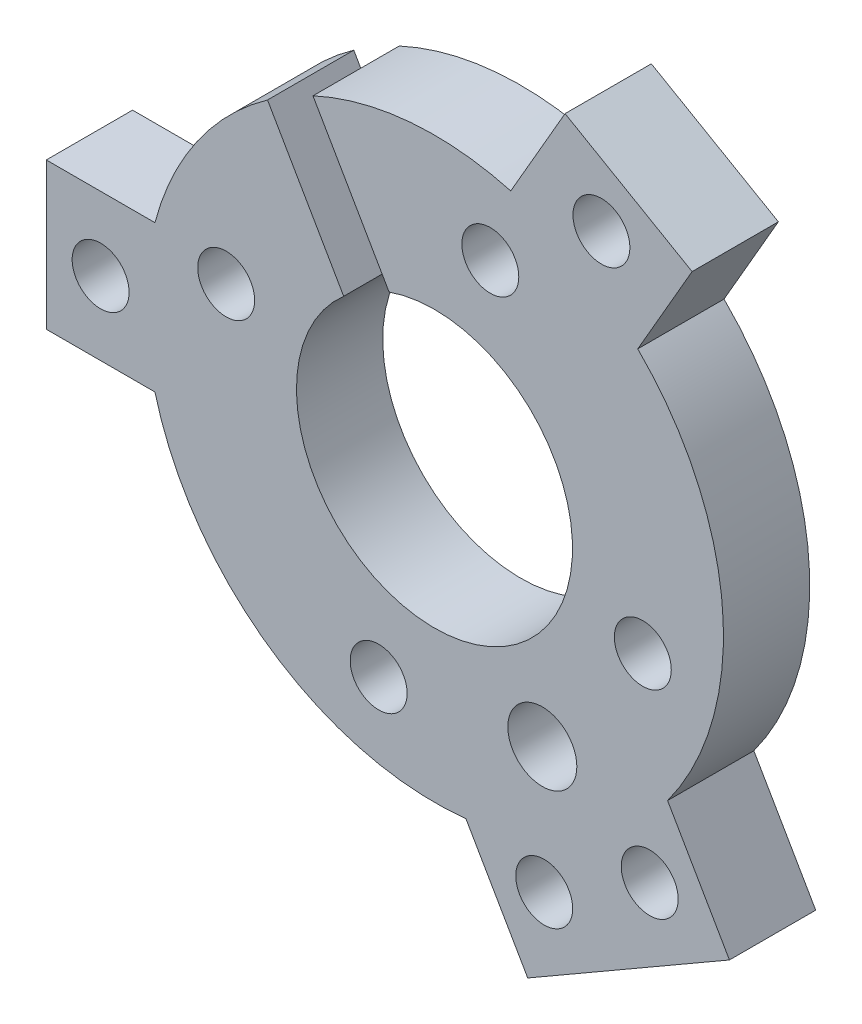
SolidWorks part; units mm, degrees
material "PET"
ref_plane "Alzado" through (0, 0, 0) normal (0, 0, 1) x (1, 0, 0)
ref_plane "Planta" through (0, 0, 0) normal (0, 1, 0) x (1, 0, 0)
ref_plane "Vista lateral" through (0, 0, 0) normal (1, 0, 0) x (0, 0, -1)
sketch "Croquis1" plane through (0, 0, 0) normal (0, 0, 1) x (1, 0, 0)
  line L0 (26.6913, -19.2308) -> (34.1913, -32.2211)
  line L1 (15.1388, 43.2211) -> (29.8612, 34.7211)
  line L2 (15.1388, 43.2211) -> (7.6388, 30.2308)
  line L3 (7.6388, 30.2308) -> (22.3612, 21.7308)
  line L4 (29.8612, 34.7211) -> (22.3612, 21.7308)
  line L5 (0, 0) -> (-34.8066, 60.2868) construction
  line L6 (0, 0) -> (-30.1609, -52.2402) construction
  line L11 (26.6913, -19.2308) -> (3.3087, -32.7308)
  line L12 (3.3087, -32.7308) -> (10.8087, -45.7211)
  line L17 (34.1913, -32.2211) -> (10.8087, -45.7211)
  line L18 (-30, -8.5) -> (-45, -8.5)
  line L19 (-30, -8.5) -> (-30, 8.5)
  line L20 (-30, 8.5) -> (-45, 8.5)
  line L21 (-45, -8.5) -> (-45, 8.5)
  line L22 (0, 0) -> (-26.6181, -46.1039) construction
  line L23 (0, 0) -> (-64.929, 0) construction
  circle A0 centre (0, 0) radius 33.5
  circle A1 centre (0, 0) radius 30 construction
  point P17 (22.5, 38.9711)
  point P23 (15, 25.9808)
  point P25 (-30, 0)
  point P27 (-45, 0)
  point P28 (22.5, -38.9711)
  point P29 (15, -25.9808)
  dimension "D1" = 67
  dimension "D2" = 60
  dimension "D3" = 27
  dimension "D4" = 15
  dimension "D5" = 15
  dimension "D6" = 15
  dimension "D7" = 17
  dimension "D8" = 17
extrude "Saliente-Extruir3" add sketch "Croquis1" along normal blind 10 contours A0 L20 L21 L18 | L20 A0 L18 L19 | L2 A0 L20 L19 L18 L12 L11 L0 L4 L3 | L4 A0 L2 L3 | A0 L4 L1 L2 | L12 A0 L0 L11 | A0 L12 L17 L0
sketch "Croquis2" plane through (0, 0, 10) normal (0, 0, 1) x (1, 0, 0)
  line L0 (0, 0) -> (11.0689, 41.3096) construction
  line L1 (0, 0) -> (-45.9889, 12.3227) construction
  line L8 (15.1388, 43.2211) -> (29.8612, 34.7211) construction
  line L9 (29.8612, 34.7211) -> (29.8612, -34.7211) construction
  line L10 (29.8612, -34.7211) -> (15.1388, -43.2211) construction
  line L11 (15.1388, -43.2211) -> (-45, -8.5) construction
  line L12 (-45, -8.5) -> (-45, 8.5) construction
  line L13 (-45, 8.5) -> (15.1388, 43.2211) construction
  line L18 (0, 0) -> (-16.75, 29.0119) construction
  line L21 (15.1388, -43.2211) -> (29.8612, -34.7211) construction
  line L23 (-19.4869, 27.5684) -> (-10.4869, 11.9799)
  line L26 (22.5, -38.9711) -> (0, 0) construction
  line L27 (-19.4869, 27.5684) -> (-14.2131, 30.6132)
  line L28 (-10.4869, 11.9799) -> (-5.2131, 15.0247)
  line L29 (-14.2131, 30.6132) -> (-5.2131, 15.0247)
  circle A0 centre (0, 0) radius 25 construction
  circle A6 centre (6.4705, 24.1481) radius 3.3
  circle A7 centre (24.1481, -6.4705) radius 3.3
  circle A8 centre (-6.4705, -24.1481) radius 3.3
  circle A9 centre (-24.1481, 6.4705) radius 3.3
  circle A10 centre (0, 0) radius 16
  circle A11 centre (12.5, -21.6506) radius 4
  circle A12 centre (24.9478, -29.0911) radius 3.3
  circle A13 centre (12.7197, -36.151) radius 3.3
  arc A14 (8.8406, 32.3124) -> (-32.4037, 8.5) centre (0, 0) ccw construction
  circle A15 centre (-38.7019, 0) radius 3.3
  circle A16 centre (19.3509, 33.5168) radius 3.3
  dimension "D1" = 50
  dimension "D2" = 6.6
  dimension "D3" = 6.6
  dimension "D12" = 32
  dimension "D13" = 8
  dimension "D4" = 6.6
  dimension "D5" = 6.6
  dimension "D6" = 3
  dimension "D7" = 18
extrude "Cortar-Extruir1" cut sketch "Croquis2" against normal through all contours A10 | A11 | A7 | A8 | A6 | A9 | A12 | A13 | L23 L27 L29 L28 | A15 | A16
